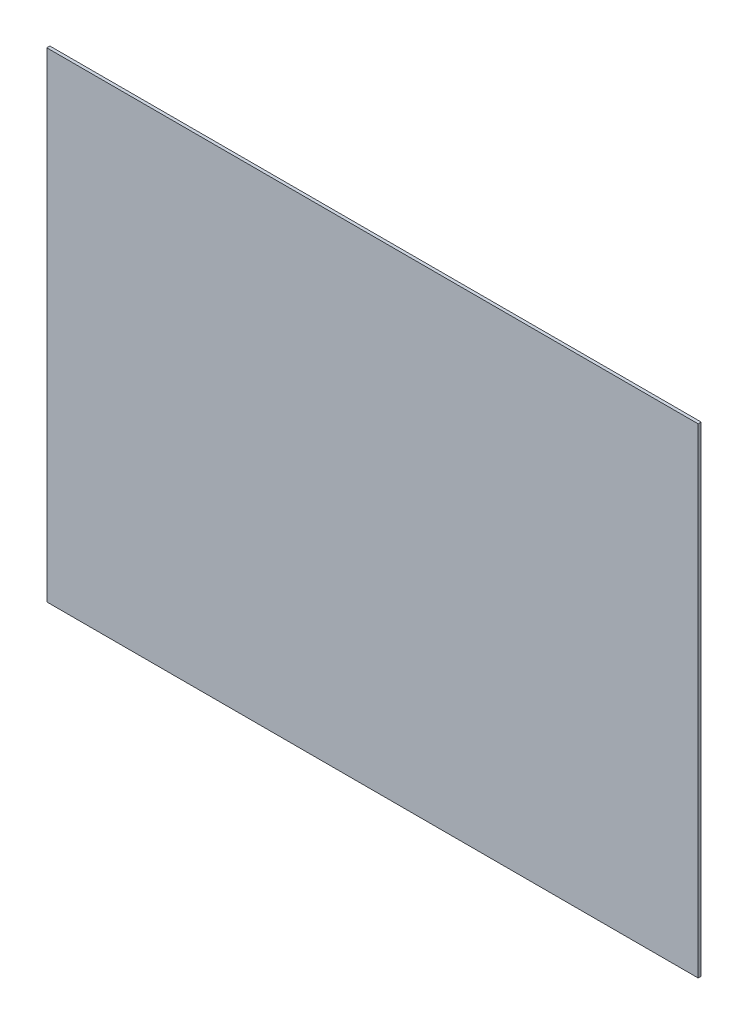
SolidWorks part; units mm, degrees
ref_plane "Спереди" through (0, 0, 0) normal (0, 0, 1) x (1, 0, 0)
ref_plane "Сверху" through (0, 0, 0) normal (0, 1, 0) x (1, 0, 0)
ref_plane "Справа" through (0, 0, 0) normal (1, 0, 0) x (0, 0, -1)
sketch "Эскиз1" plane through (0, 0, 0) normal (0, 0, 1) x (1, 0, 0)
  line L1 (-1900, -1400) -> (1900, -1400)
  line L2 (-1900, -1400) -> (-1900, 1400)
  line L3 (-1900, 1400) -> (1900, 1400)
  line L4 (1900, -1400) -> (1900, 1400)
  line L5 (0, 1400) -> (0, -1400) construction
  line L6 (-1900, 0) -> (1900, 0) construction
  point P0 (0, 0)
  dimension "D1" = 3800
  dimension "D2" = 2800
extrude "Бобышка-Вытянуть1" add sketch "Эскиз1" along normal blind 18
